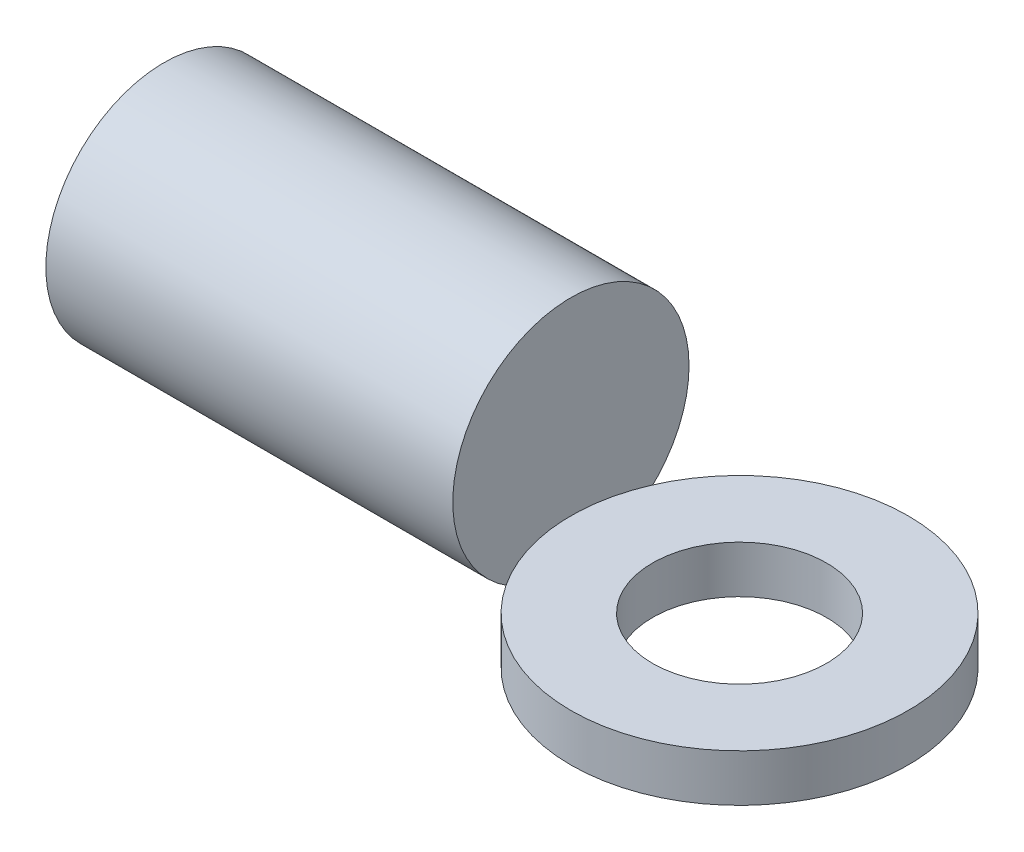
SolidWorks part; units mm, degrees
ref_plane "Front Plane" through (0, 0, 0) normal (0, 0, 1) x (1, 0, 0)
ref_plane "Top Plane" through (0, 0, 0) normal (0, 1, 0) x (1, 0, 0)
ref_plane "Right Plane" through (0, 0, 0) normal (1, 0, 0) x (0, 0, -1)
sketch "Sketch1" plane through (0, 0, 0) normal (0, 1, 0) x (1, 0, 0)
  line L0 (-2.1142, 2.875) -> (-12.1793, 2.875) construction
  line L1 (-12.1793, 2.875) -> (-12.1793, -2.875) construction
  line L2 (-12.1793, -2.875) -> (-2.1142, -2.875) construction
  line L3 (-12.1793, 0) -> (0, 0) construction
  circle A0 centre (0, 0) radius 1.8415
  arc A1 (-2.1142, -2.875) -> (-2.1142, 2.875) centre (0, 0) ccw
  arc A2 (-2.1142, 2.875) -> (-2.1142, -2.875) centre (0, 0) ccw
  dimension "D1" = 3.683
  dimension "D2" = 7.1374
  dimension "D3" = 12.1793
  dimension "D4" = 5.75
ref_plane "Plane2" through (-12.18, 0, 0) normal (1, 0, 0) x (0, 0, -1)
ref_plane "Plane3" through (-3.5687, 0, 0) normal (1, 0, 0) x (0, 0, -1)
sketch "Sketch18" plane through (-12.18, 0, 0) normal (1, 0, 0) x (0, 0, -1)
  line L0 (0, 2.5) -> (0, 0) construction
  circle A0 centre (0, 2.5) radius 2.5
  dimension "D1" = 5
extrude "Boss-Extrude4" add sketch "Sketch18" along normal up to surface (8.6113 mm away) up to plane "Plane3"
extrude "Boss-Extrude5" add sketch "Sketch1" along normal blind 1 separate body
